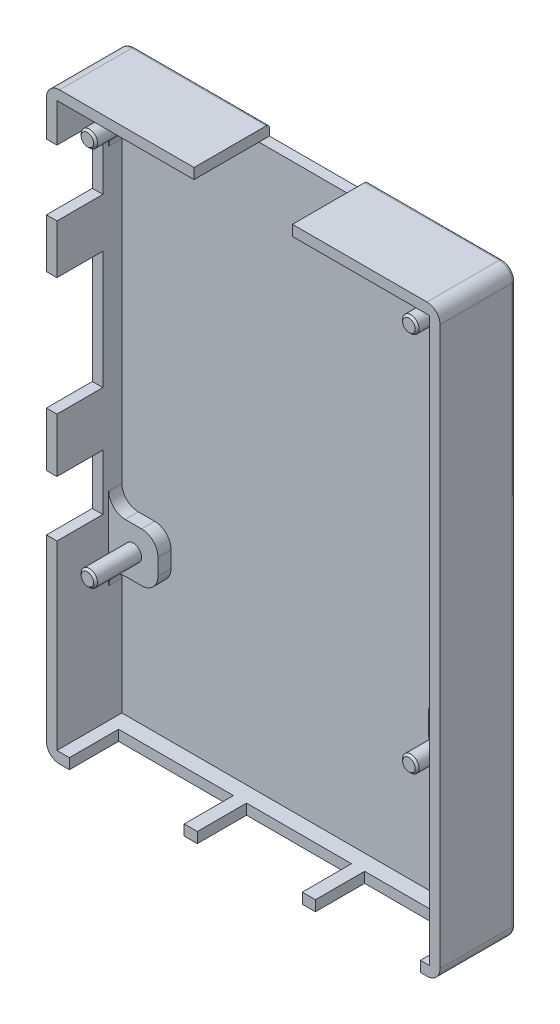
SolidWorks part; units mm, degrees
ref_plane "Plan de face" through (0, 0, 0) normal (0, 0, 1) x (1, 0, 0)
ref_plane "Plan de dessus" through (0, 0, 0) normal (0, 1, 0) x (1, 0, 0)
ref_plane "Plan de droite" through (0, 0, 0) normal (1, 0, 0) x (0, 0, -1)
ref_plane "Plan1" through (0, 0, 5.75) normal (0, 0, 1) x (1, 0, 0)
sketch "Esquisse1" plane through (0, 0, 5.75) normal (0, 0, 1) x (1, 0, 0)
  line L0 (30, 44.5) -> (-30, 44.5)
  line L1 (-30, 44.5) -> (-30, -44.5)
  line L2 (-30, -44.5) -> (30, -44.5)
  line L3 (30, -44.5) -> (30, 44.5)
extrude "Boss.-Extru.1" add sketch "Esquisse1" against normal blind 11.5
sketch "Esquisse2" plane through (0, 0, -5.75) normal (0, 0, -1) x (-1, 0, 0)
  line L0 (-7.5, 44.5) -> (-7.5, 42.9)
  line L1 (-7.5, 42.9) -> (7.5, 42.9)
  line L2 (7.5, 42.9) -> (7.5, 44.5)
  line L3 (7.5, 44.5) -> (-7.5, 44.5)
extrude "Enlèv. mat.-Extru.1" cut sketch "Esquisse2" against normal through all
ref_plane "Plan2" through (0, 42.9, 0) normal (0, 1, 0) x (1, 0, 0)
ref_plane "Plan3" through (0, -42.9, 0) normal (0, -1, 0) x (1, 0, 0)
sketch "Esquisse4" plane through (0, -42.9, 0) normal (0, -1, 0) x (1, 0, 0)
  line L0 (-7.5, 5.75) -> (-7.5, -4.15)
  line L1 (-7.5, -4.15) -> (7.5, -4.15)
  line L2 (7.5, -4.15) -> (7.5, 5.75)
  line L3 (7.5, 5.75) -> (-7.5, 5.75)
extrude "Enlèv. mat.-Extru.2" cut sketch "Esquisse4" against normal up to surface up to plane "Plan2"
ref_plane "Plan4" through (-28.4, 0, 0) normal (-1, 0, 0) x (0, -1, 0)
sketch "Esquisse5" plane through (-28.4, 0, 0) normal (-1, 0, 0) x (0, -1, 0)
  line L0 (42.9, 5.75) -> (-42.9, 5.75)
  line L1 (-42.9, 5.75) -> (-42.9, -4.15)
  line L2 (-42.9, -4.15) -> (42.9, -4.15)
  line L3 (42.9, -4.15) -> (42.9, 5.75)
extrude "Enlèv. mat.-Extru.3" cut sketch "Esquisse5" against normal up to next
ref_plane "Plan5" through (28.4, 0, 0) normal (1, 0, 0) x (0, 0, -1)
sketch "Esquisse6" plane through (28.4, 0, 0) normal (1, 0, 0) x (0, 0, -1)
  line L0 (4.15, 42.9) -> (-5.75, 42.9)
  line L1 (-5.75, 42.9) -> (-5.75, -42.9)
  line L2 (-5.75, -42.9) -> (4.15, -42.9)
  line L3 (4.15, -42.9) -> (4.15, 42.9)
extrude "Enlèv. mat.-Extru.4" cut sketch "Esquisse6" against normal up to next
sketch "Esquisse7" plane through (-30, 0, 0) normal (-1, 0, 0) x (0, 0, 1)
  line L0 (5.75, 27) -> (5.75, 37)
  line L1 (5.75, 37) -> (-1.25, 37)
  line L2 (-1.25, 37) -> (-1.25, 27)
  line L3 (-1.25, 27) -> (5.75, 27)
extrude "Enlèv. mat.-Extru.5" cut sketch "Esquisse7" against normal up to next
sketch "Esquisse8" plane through (-30, 0, 0) normal (-1, 0, 0) x (0, 0, 1)
  line L0 (5.75, 1.5) -> (5.75, 19.5)
  line L1 (5.75, 19.5) -> (-1.25, 19.5)
  line L2 (-1.25, 19.5) -> (-1.25, 1.5)
  line L3 (-1.25, 1.5) -> (5.75, 1.5)
extrude "Enlèv. mat.-Extru.6" cut sketch "Esquisse8" against normal up to next
sketch "Esquisse9" plane through (0, -44.5, 0) normal (0, -1, 0) x (1, 0, 0)
  line L0 (-9, 5.75) -> (-26.5, 5.75)
  line L1 (-26.5, 5.75) -> (-26.5, -1.75)
  line L2 (-26.5, -1.75) -> (-9, -1.75)
  line L3 (-9, -1.75) -> (-9, 5.75)
extrude "Enlèv. mat.-Extru.7" cut sketch "Esquisse9" against normal up to next
sketch "Esquisse10" plane through (0, -44.5, 0) normal (0, -1, 0) x (1, 0, 0)
  line L0 (9, 5.75) -> (-7, 5.75)
  line L1 (-7, 5.75) -> (-7, -1.75)
  line L2 (-7, -1.75) -> (9, -1.75)
  line L3 (9, -1.75) -> (9, 5.75)
extrude "Enlèv. mat.-Extru.8" cut sketch "Esquisse10" against normal up to next
sketch "Esquisse11" plane through (0, -44.5, 0) normal (0, -1, 0) x (1, 0, 0)
  line L0 (27, 5.75) -> (11, 5.75)
  line L1 (11, 5.75) -> (11, -1.75)
  line L2 (11, -1.75) -> (27, -1.75)
  line L3 (27, -1.75) -> (27, 5.75)
extrude "Enlèv. mat.-Extru.9" cut sketch "Esquisse11" against normal up to next
sketch "Esquisse12" plane through (-30, 0, 0) normal (-1, 0, 0) x (0, 0, 1)
  line L0 (5.75, -15.25) -> (5.75, -6.75)
  line L1 (5.75, -6.75) -> (-1.25, -6.75)
  line L2 (-1.25, -6.75) -> (-1.25, -15.25)
  line L3 (-1.25, -15.25) -> (5.75, -15.25)
extrude "Enlèv. mat.-Extru.10" cut sketch "Esquisse12" against normal up to next
ref_plane "Plan6" through (0, 0, -5.65) normal (0, 0, 1) x (1, 0, 0)
ref_plane "Plan7" through (0, 0, -3.15) normal (0, 0, -1) x (0, 1, 0)
sketch "Esquisse23" plane through (-28.4, 0, 0) normal (1, 0, 0) x (0, 0, -1)
  line L0 (2.15, 42.9) -> (4.15, 42.9)
  line L1 (4.15, 42.9) -> (4.15, 35.4)
  line L2 (4.15, 35.4) -> (2.15, 35.4)
  line L3 (2.15, 35.4) -> (2.15, 42.9)
extrude "Boss.-Extru.5" add sketch "Esquisse23" along normal blind 7.5
sketch "Esquisse24" plane through (0, 42.9, 0) normal (0, -1, 0) x (1, 0, 0)
  line L0 (28.4, -2.15) -> (28.4, -4.15)
  line L1 (28.4, -4.15) -> (20.9, -4.15)
  line L2 (20.9, -4.15) -> (20.9, -2.15)
  line L3 (20.9, -2.15) -> (28.4, -2.15)
extrude "Boss.-Extru.6" add sketch "Esquisse24" along normal blind 7.5
sketch "Esquisse25" plane through (28.4, 0, 0) normal (-1, 0, 0) x (0, 0, 1)
  line L0 (-4.15, -15.1) -> (-2.15, -15.1)
  line L1 (-2.15, -15.1) -> (-2.15, -22.6)
  line L2 (-2.15, -22.6) -> (-4.15, -22.6)
  line L3 (-4.15, -22.6) -> (-4.15, -15.1)
extrude "Boss.-Extru.7" add sketch "Esquisse25" along normal blind 8.1
sketch "Esquisse26" plane through (-28.4, 0, 0) normal (1, 0, 0) x (0, 0, -1)
  line L0 (2.15, -15.1) -> (4.15, -15.1)
  line L1 (4.15, -15.1) -> (4.15, -22.6)
  line L2 (4.15, -22.6) -> (2.15, -22.6)
  line L3 (2.15, -22.6) -> (2.15, -15.1)
extrude "Boss.-Extru.8" add sketch "Esquisse26" along normal blind 7.5
ref_plane "Plan8" through (0, -18.85, 0) normal (0, 1, 0) x (1, 0, 0)
sketch "Esquisse28" plane through (0, -18.85, 0) normal (0, 1, 0) x (1, 0, 0)
  line L0 (25.6, 2.15) -> (24.35, 2.15)
  line L1 (24.35, 2.15) -> (24.35, -4.85)
  line L2 (24.35, -4.85) -> (25.6, -4.85)
  line L3 (25.6, -4.85) -> (25.6, 2.15)
  line L4 (24.35, 2.15) -> (24.35, -4.85) construction
revolve "Révolution1" add sketch "Esquisse28" angle 360 about L4
ref_plane "Plan9" through (0, 39.15, 0) normal (0, 1, 0) x (1, 0, 0)
sketch "Esquisse29" plane through (0, 39.15, 0) normal (0, 1, 0) x (1, 0, 0)
  line L0 (25.6, 2.15) -> (24.35, 2.15)
  line L1 (24.35, 2.15) -> (24.35, -4.85)
  line L2 (24.35, -4.85) -> (25.6, -4.85)
  line L3 (25.6, -4.85) -> (25.6, 2.15)
  line L4 (24.35, 2.15) -> (24.35, -4.85) construction
revolve "Révolution2" add sketch "Esquisse29" angle 360 about L4
sketch "Esquisse30" plane through (0, 39.15, 0) normal (0, 1, 0) x (1, 0, 0)
  line L0 (-23.4, 2.15) -> (-24.65, 2.15)
  line L1 (-24.65, 2.15) -> (-24.65, -4.85)
  line L2 (-24.65, -4.85) -> (-23.4, -4.85)
  line L3 (-23.4, -4.85) -> (-23.4, 2.15)
  line L4 (-24.65, 2.15) -> (-24.65, -4.85) construction
revolve "Révolution3" add sketch "Esquisse30" angle 360 about L4
sketch "Esquisse31" plane through (0, -18.85, 0) normal (0, 1, 0) x (1, 0, 0)
  line L0 (-23.4, 2.15) -> (-24.65, 2.15)
  line L1 (-24.65, 2.15) -> (-24.65, -4.85)
  line L2 (-24.65, -4.85) -> (-23.4, -4.85)
  line L3 (-23.4, -4.85) -> (-23.4, 2.15)
  line L4 (-24.65, 2.15) -> (-24.65, -4.85) construction
revolve "Révolution4" add sketch "Esquisse31" angle 360 about L4
fillet "Congé1" radius 2 4 edges at (30, 44.5, 0) (-30, 44.5, 0) (30, -44.5, 0) (-30, -44.5, 0)
chamfer "Chanfrein1" distance 0.3 angle 45 4 edges at (25.6, -18.85, 4.85) (-23.4, 39.15, 4.85) (-23.4, -18.85, 4.85) (25.6, 39.15, 4.85)
fillet "Congé2" radius 0.5 9 edges at (-17.75, 44.5, -5.75) (-29.4142, 43.9142, -5.75) (-30, 0, -5.75) (-29.4142, -43.9142, -5.75) (0, -44.5, -5.75) (29.4142, -43.9142, -5.75) (30, 0, -5.75) (17.75, 44.5, -5.75) (29.4142, 43.9142, -5.75)
fillet "Congé9" radius 2.5 14 edges at (-28.4, 35.4, -3.15) (20.9, 35.4, -3.15) (-20.9, 42.9, -3.15) (20.3, -22.6, -3.15) (-28.4, -15.1, -3.15) (28.4, -22.6, -3.15) (-20.9, 35.4, -3.15) (-28.4, -22.6, -3.15) (20.9, 42.9, -3.15) (-20.9, -22.6, -3.15) (20.3, -15.1, -3.15) (28.4, 35.4, -3.15) (-20.9, -15.1, -3.15) (28.4, -15.1, -3.15)
